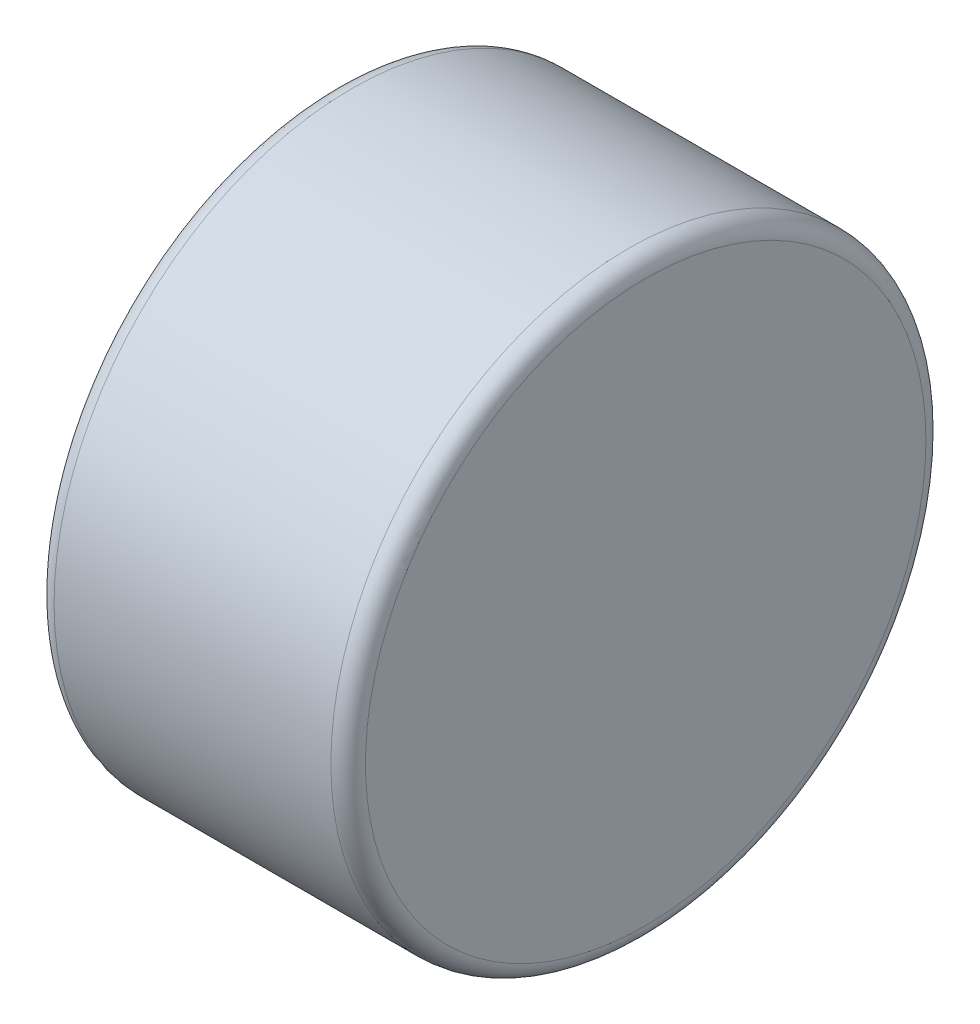
SolidWorks part; units mm, degrees
ref_plane "Front Plane" through (0, 0, 0) normal (0, 0, 1) x (1, 0, 0)
ref_plane "Top Plane" through (0, 0, 0) normal (0, 1, 0) x (1, 0, 0)
ref_plane "Right Plane" through (0, 0, 0) normal (1, 0, 0) x (0, 0, -1)
sketch "Sketch2" plane through (0, 0, 0) normal (1, 0, 0) x (0, 0, -1)
  circle A0 centre (0, 0) radius 34.4
  dimension "D1" = 68.8
extrude "Boss-Extrude1" add sketch "Sketch2" along normal blind 36
fillet "Fillet1" radius 2 2 edges at (36, 0, -34.4) (0, 0, -34.4)
